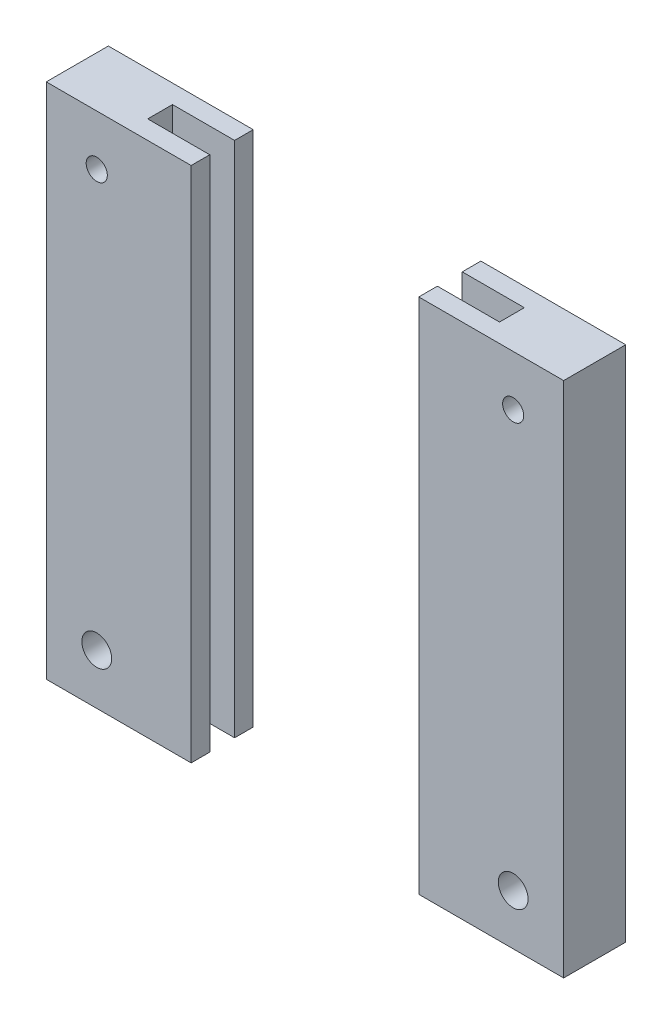
SolidWorks part; units mm, degrees
material "1060 Alloy"
ref_plane "Front Plane" through (0, 0, 0) normal (0, 0, 1) x (1, 0, 0)
ref_plane "Top Plane" through (0, 0, 0) normal (0, 1, 0) x (1, 0, 0)
ref_plane "Right Plane" through (0, 0, 0) normal (1, 0, 0) x (0, 0, -1)
sketch "Sketch1" plane through (0, 0, 0) normal (0, 0, 1) x (1, 0, 0)
  line L1 (0, 0) -> (125, 0)
  line L2 (0, 0) -> (0, 125)
  line L3 (0, 125) -> (125, 125)
  line L4 (125, 0) -> (125, 125)
  dimension "D1" = 125
  dimension "D2" = 125
extrude "Plate" add sketch "Sketch1" along normal blind 15 contours L3 L4 L1 L2
sketch "Sketch2" plane through (0, 125, 0) normal (0, 1, 0) x (1, 0, 0)
  line L0 (0, -15) -> (0, 0) construction
  line L1 (20, -4.5) -> (35, -4.5)
  line L2 (20, -4.5) -> (20, -10.5)
  line L3 (20, -10.5) -> (35, -10.5)
  line L4 (35, -4.5) -> (35, -10.5)
  line L5 (0, 0) -> (125, 0) construction
  line L6 (20, -4.5) -> (20, 0) construction
  line L7 (20, -10.5) -> (20, -15) construction
  line L8 (0, -15) -> (125, -15) construction
  dimension "D1" = 15
  dimension "D2" = 6
  dimension "D3" = 20
extrude "Cut-Extrude1" cut sketch "Sketch2" against normal through all both and the other way through all
ref_plane "midplane" through (62.5, 0, 0) normal (1, 0, 0) x (0, 0, -1)
mirror "Mirror1" about plane through (62.5, 0, 0) normal (1, 0, 0) of "Cut-Extrude1"
sketch "Sketch3" plane through (0, 125, 0) normal (0, 1, 0) x (1, 0, 0)
  line L0 (0, 0) -> (125, 0) construction
  line L1 (35, 0) -> (90, 0)
  line L2 (35, 0) -> (35, -15)
  line L3 (35, -15) -> (90, -15)
  line L4 (90, 0) -> (90, -15)
  line L5 (0, -15) -> (125, -15) construction
extrude "Cut-Extrude2" cut sketch "Sketch3" against normal through all
ref_plane "Plane1" through (0, 0, 7.5) normal (0, 0, -1) x (-1, 0, 0)
sketch "Sketch4" plane through (0, 0, 0) normal (0, 0, -1) x (-1, 0, 0)
  line L0 (-125, 0) -> (-125, 125) construction
  line L1 (-90, 125) -> (-125, 125) construction
  line L2 (-90, 0) -> (-125, 0) construction
  circle A0 centre (-112.8, 12.2) radius 3.6
  circle A1 centre (-112.8, 112.8) radius 2.55
  dimension "D5" = 7.2
  dimension "D6" = 5.1
  dimension "D1" = 12.2
  dimension "D2" = 12.2
  dimension "D3" = 12.2
  dimension "D4" = 12.2
extrude "Cut-Extrude3" cut sketch "Sketch4" against normal through all both and the other way through all
mirror "Mirror2" about plane through (62.5, 0, 0) normal (1, 0, 0) of "Cut-Extrude3"
